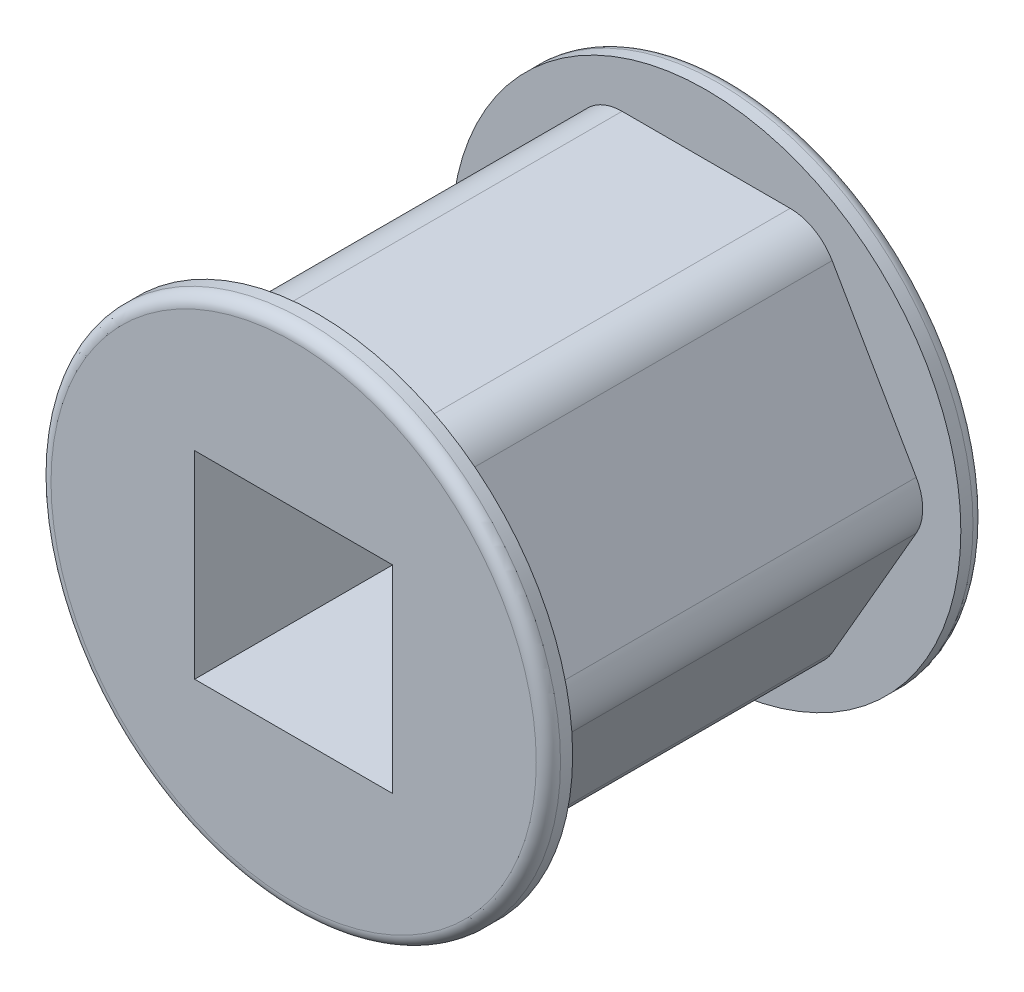
SolidWorks part; units mm, degrees
ref_plane "Front Plane" through (0, 0, 0) normal (0, 0, 1) x (1, 0, 0)
ref_plane "Top Plane" through (0, 0, 0) normal (0, 1, 0) x (1, 0, 0)
ref_plane "Right Plane" through (0, 0, 0) normal (1, 0, 0) x (0, 0, -1)
sketch "Sketch1" plane through (0, 0, 0) normal (0, 0, 1) x (1, 0, 0)
  line L1 (-3.2385, -3.2385) -> (3.2385, -3.2385)
  line L2 (-3.2385, -3.2385) -> (-3.2385, 3.2385)
  line L3 (-3.2385, 3.2385) -> (3.2385, 3.2385)
  line L4 (3.2385, -3.2385) -> (3.2385, 3.2385)
  line L5 (-3.2385, -3.2385) -> (3.2385, 3.2385) construction
  line L6 (-3.2385, 3.2385) -> (3.2385, -3.2385) construction
  circle A0 centre (0, 0) radius 8.3344
  dimension "D1" = 16.6687
  dimension "D2" = 6.477
extrude "Boss-Extrude1" add sketch "Sketch1" along normal blind 0.7937
sketch "Sketch2" plane through (0, 0, 0.7937) normal (0, 0, 1) x (1, 0, 0)
  line L1 (7.3323, 0) -> (3.6662, 6.35)
  line L2 (3.6662, 6.35) -> (-3.6662, 6.35)
  line L3 (-3.6662, 6.35) -> (-7.3323, 0)
  line L4 (-7.3323, 0) -> (-3.6662, -6.35)
  line L5 (-3.6662, -6.35) -> (3.6662, -6.35)
  line L6 (3.6662, -6.35) -> (7.3323, 0)
  line L7 (3.2385, -3.2385) -> (-3.2385, -3.2385)
  line L8 (3.2385, -3.2385) -> (3.2385, 3.2385)
  line L9 (3.2385, 3.2385) -> (-3.2385, 3.2385)
  line L10 (-3.2385, -3.2385) -> (-3.2385, 3.2385)
  line L11 (3.2385, -3.2385) -> (-3.2385, 3.2385) construction
  line L12 (3.2385, 3.2385) -> (-3.2385, -3.2385) construction
  circle A0 centre (0, 0) radius 6.35 construction
  dimension "D1" = 12.7
extrude "Boss-Extrude2" add sketch "Sketch2" along normal blind 6.35
sketch "Sketch3" plane through (0, 0, 0) normal (0, 0, -1) x (-1, 0, 0)
  circle A0 centre (0, 0) radius 5.1435
  dimension "D1" = 10.287
extrude "Cut-Extrude1" cut sketch "Sketch3" against normal blind 1.27
fillet "Fillet1" radius 1.5875 6 edges at (-7.3323, 0, 3.9688) (-3.6662, -6.35, 3.9688) (3.6662, -6.35, 3.9688) (7.3323, 0, 3.9688) (3.6662, 6.35, 3.9688) (-3.6662, 6.35, 3.9688)
fillet "Fillet2" radius 0.3969 1 edges at (8.3344, 0, 0)
mirror "Mirror1" about plane through (0, 0, 7.1437) normal (0, 0, 1) of bodies 104 102
sketch "Sketch5" plane through (0, 0, 1.27) normal (0, 0, -1) x (-1, 0, 0)
  line L0 (3.2385, -3.2385) -> (3.2385, 3.2385) construction
  line L1 (-3.2385, -3.2385) -> (3.2385, -3.2385) construction
  line L2 (-3.2385, 3.2385) -> (-3.2385, -3.2385) construction
  line L3 (3.2385, 3.2385) -> (-3.2385, 3.2385) construction
  line L4 (3.2385, -3.2385) -> (3.2385, 3.2385)
  line L5 (-3.2385, -3.2385) -> (3.2385, -3.2385)
  line L6 (-3.2385, 3.2385) -> (-3.2385, -3.2385)
  line L7 (3.2385, 3.2385) -> (-3.2385, 3.2385)
  circle A1 centre (0, 0) radius 5.1435
  circle A2 centre (0, 0) radius 5.1435
  dimension "D1" = 0
extrude "Boss-Extrude3" add sketch "Sketch5" along normal up to surface (1.27 mm away) up to face at (7.9375, 0, 0)
sketch "Sketch6" plane through (0, 0, 13.0175) normal (0, 0, 1) x (1, 0, 0)
  line L0 (3.2385, 3.2385) -> (3.2385, -3.2385) construction
  line L1 (3.2385, -3.2385) -> (-3.2385, -3.2385) construction
  line L2 (-3.2385, -3.2385) -> (-3.2385, 3.2385) construction
  line L3 (-3.2385, 3.2385) -> (3.2385, 3.2385) construction
  line L4 (3.2385, 3.2385) -> (3.2385, -3.2385)
  line L5 (3.2385, -3.2385) -> (-3.2385, -3.2385)
  line L6 (-3.2385, -3.2385) -> (-3.2385, 3.2385)
  line L7 (-3.2385, 3.2385) -> (3.2385, 3.2385)
  circle A1 centre (0, 0) radius 5.1435
  circle A2 centre (0, 0) radius 5.1435
  dimension "D1" = 0
extrude "Boss-Extrude4" add sketch "Sketch6" along normal up to surface (1.27 mm away) up to face at (7.9375, 0, 14.2875)
